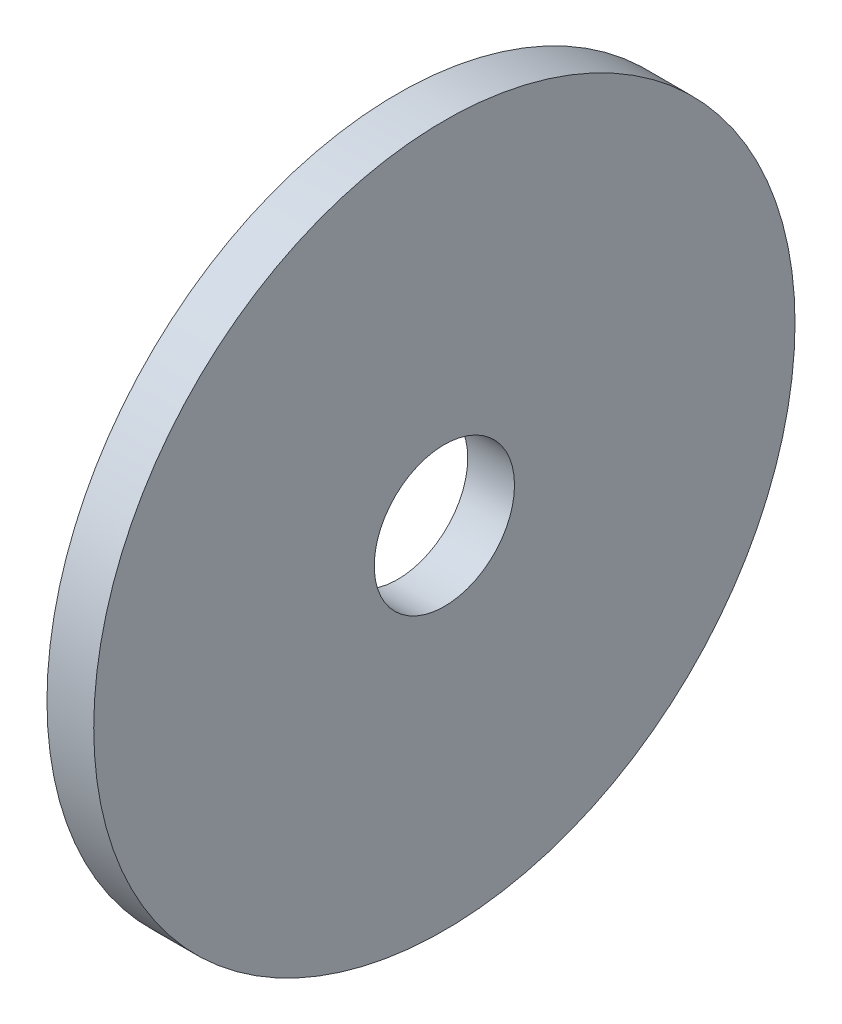
SolidWorks part; units mm, degrees
material "ASTM A36 Steel"
ref_plane "Front Plane" through (0, 0, 0) normal (0, 0, 1) x (1, 0, 0)
ref_plane "Top Plane" through (0, 0, 0) normal (0, 1, 0) x (1, 0, 0)
ref_plane "Right Plane" through (0, 0, 0) normal (1, 0, 0) x (0, 0, -1)
sketch "Sketch1" plane through (0, 0, 0) normal (1, 0, 0) x (0, 0, -1)
  circle A0 centre (0, 0) radius 30
  circle A1 centre (0, 0) radius 6
  dimension "D1" = 60
  dimension "D2" = 12
extrude "Boss-Extrude1" add sketch "Sketch1" along normal mid plane 4
